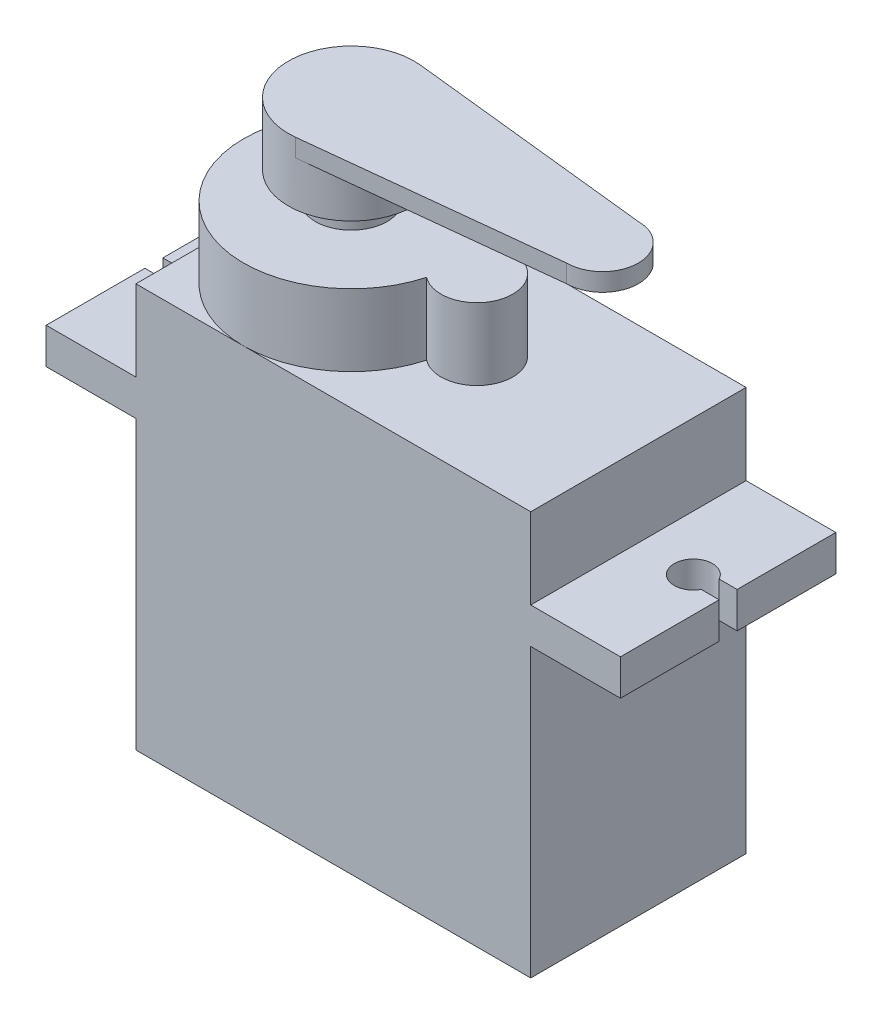
SolidWorks part; units mm, degrees
material "Custom Plastic"
ref_plane "Front Plane" through (0, 0, 0) normal (0, 0, 1) x (1, 0, 0)
ref_plane "Top Plane" through (0, 0, 0) normal (0, 1, 0) x (1, 0, 0)
ref_plane "Right Plane" through (0, 0, 0) normal (1, 0, 0) x (0, 0, -1)
sketch "Sketch1" plane through (0, 0, 0) normal (0, 1, 0) x (1, 0, 0)
  line L1 (-11, 6) -> (11, 6)
  line L2 (-11, 6) -> (-11, -6)
  line L3 (-11, -6) -> (11, -6)
  line L4 (11, 6) -> (11, -6)
  line L5 (-11, 6) -> (11, -6) construction
  line L6 (-11, -6) -> (11, 6) construction
  point P0 (0, 0)
  dimension "D1" = 22
  dimension "D2" = 12
extrude "Boss-Extrude1" add sketch "Sketch1" along normal blind 22.5
sketch "Sketch2" plane through (-11, 0, 0) normal (-1, 0, 0) x (0, 0, 1)
  line L0 (6, 22.5) -> (6, 0) construction
  line L1 (6, 18) -> (-6, 18)
  line L2 (6, 18) -> (6, 16)
  line L3 (6, 16) -> (-6, 16)
  line L4 (-6, 18) -> (-6, 16)
  line L5 (-6, 22.5) -> (-6, 0) construction
  line L6 (-6, 0) -> (6, 0) construction
  dimension "D1" = 16
  dimension "D2" = 2
extrude "Boss-Extrude2" add sketch "Sketch2" along normal blind 5
sketch "Sketch3" plane through (0, 18, 0) normal (0, 1, 0) x (1, 0, 0)
  line L0 (-16, -6) -> (-16, 6) construction
  line L1 (-16, 0.5) -> (-16, -0.5)
  line L2 (-16, 0.5) -> (-15, 0.5)
  line L3 (-16, -0.5) -> (-15, -0.5)
  arc A0 (-15, -0.5) -> (-15, 0.5) centre (-14.0625, 0) ccw
  point P0 (-16, 0)
  point P6 (-16, 0)
  point P9 (-13, 0)
  dimension "D1" = 1
  dimension "D2" = 1
  dimension "D3" = 1
  dimension "D4" = 3
extrude "Cut-Extrude1" cut sketch "Sketch3" against normal up to next
mirror "Mirror1" about plane through (0, 0, 0) normal (1, 0, 0) of "Cut-Extrude1", "Boss-Extrude2"
sketch "Sketch4" plane through (0, 22.5, 0) normal (0, 1, 0) x (1, 0, 0)
  line L0 (-11, 6) -> (-11, -6) construction
  circle A0 centre (-5, 0) radius 6
  dimension "D1" = 12
  dimension "D2" = 6
extrude "Boss-Extrude3" add sketch "Sketch4" along normal blind 4
sketch "Sketch5" plane through (0, 22.5, 0) normal (0, 1, 0) x (1, 0, 0)
  circle A0 centre (2, 0) radius 2
  arc A1 (-5, -6) -> (-5, 6) centre (-5, 0) ccw construction
  point P2 (4, 0)
  point P3 (1, 0)
  dimension "D1" = 3
extrude "Boss-Extrude4" add sketch "Sketch5" along normal blind 4
sketch "Sketch6" plane through (0, 26.5, 0) normal (0, 1, 0) x (1, 0, 0)
  circle A0 centre (-5, 0) radius 2
extrude "Boss-Extrude5" add sketch "Sketch6" along normal blind 1.5
sketch "Sketch7" plane through (0, 28, 0) normal (0, 1, 0) x (1, 0, 0)
  circle A0 centre (-5, 0) radius 3.5
  dimension "D1" = 7
extrude "Boss-Extrude6" add sketch "Sketch7" along normal blind 3.5
sketch "Sketch8" plane through (0, 31.5, 0) normal (0, 1, 0) x (1, 0, 0)
  line L0 (-4.6221, 3.4795) -> (-4.6221, -3.4795)
  line L1 (-4.6221, 3.4795) -> (9, 2)
  line L2 (-4.6221, -3.4795) -> (9, -2)
  arc A0 (9, -2) -> (9, 2) centre (9, 0) ccw
  circle A1 centre (-5, 0) radius 3.5 construction
  dimension "D1" = 4
extrude "Boss-Extrude7" add sketch "Sketch8" against normal blind 1
sketch "Sketch9" plane through (-11, 0, 0) normal (-1, 0, 0) x (0, 0, 1)
  line L0 (6, 16) -> (6, 0) construction
  line L1 (-2, 5) -> (2, 5)
  line L2 (-2, 5) -> (-2, 4)
  line L3 (-2, 4) -> (2, 4)
  line L4 (2, 5) -> (2, 4)
  line L5 (-2, 5) -> (2, 4) construction
  line L6 (-2, 4) -> (2, 5) construction
  line L7 (-6, 16) -> (-6, 0) construction
  line L8 (-6, 0) -> (6, 0) construction
  point P0 (0, 4.5)
  dimension "D1" = 4
  dimension "D2" = 4
  dimension "D3" = 4
  dimension "D4" = 5
